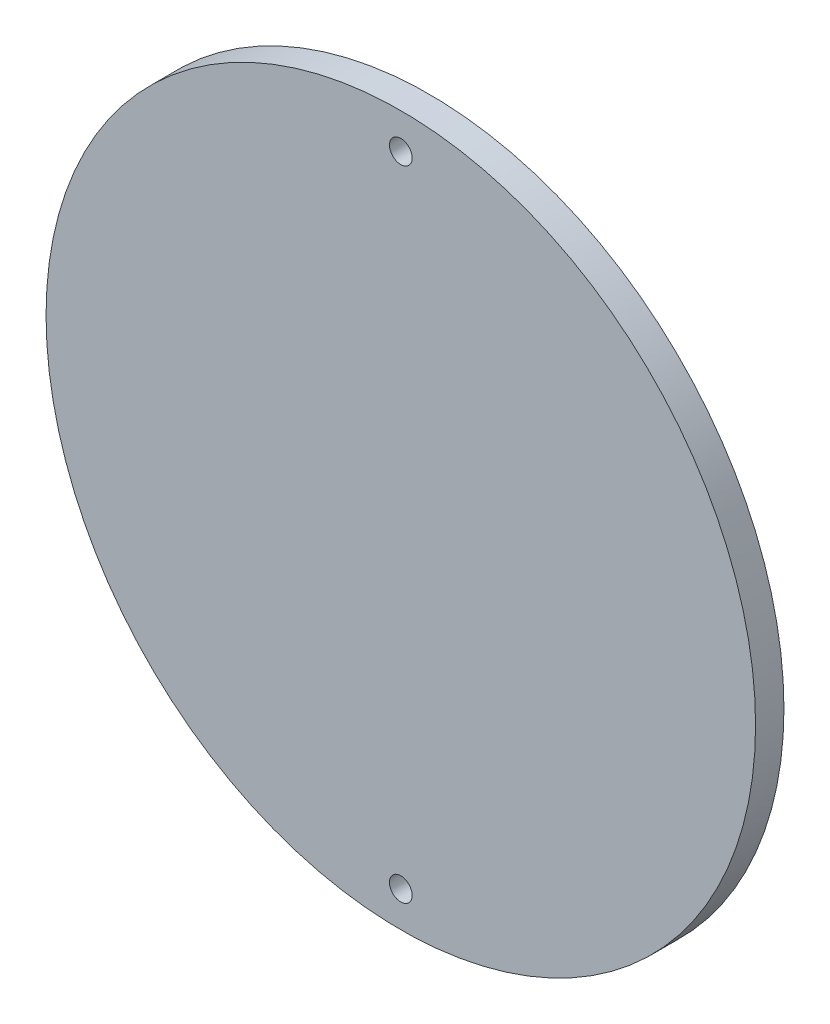
SolidWorks part; units mm, degrees
ref_plane "前视基准面" through (0, 0, 0) normal (0, 0, 1) x (1, 0, 0)
ref_plane "上视基准面" through (0, 0, 0) normal (0, 1, 0) x (1, 0, 0)
ref_plane "右视基准面" through (0, 0, 0) normal (1, 0, 0) x (0, 0, -1)
sketch "草图1" plane through (0, 0, 0) normal (0, 0, 1) x (1, 0, 0)
  circle A0 centre (0, 0) radius 50
  circle A1 centre (0, 45) radius 1.6
  circle A2 centre (0, -45) radius 1.6
  point P6 (0, 0)
  dimension "D1" = 100
  dimension "D2" = 3.2
  dimension "D3" = 3.2
  dimension "D4" = 45
  dimension "D5" = 45
extrude "凸台-拉伸1" add sketch "草图1" along normal blind 4
